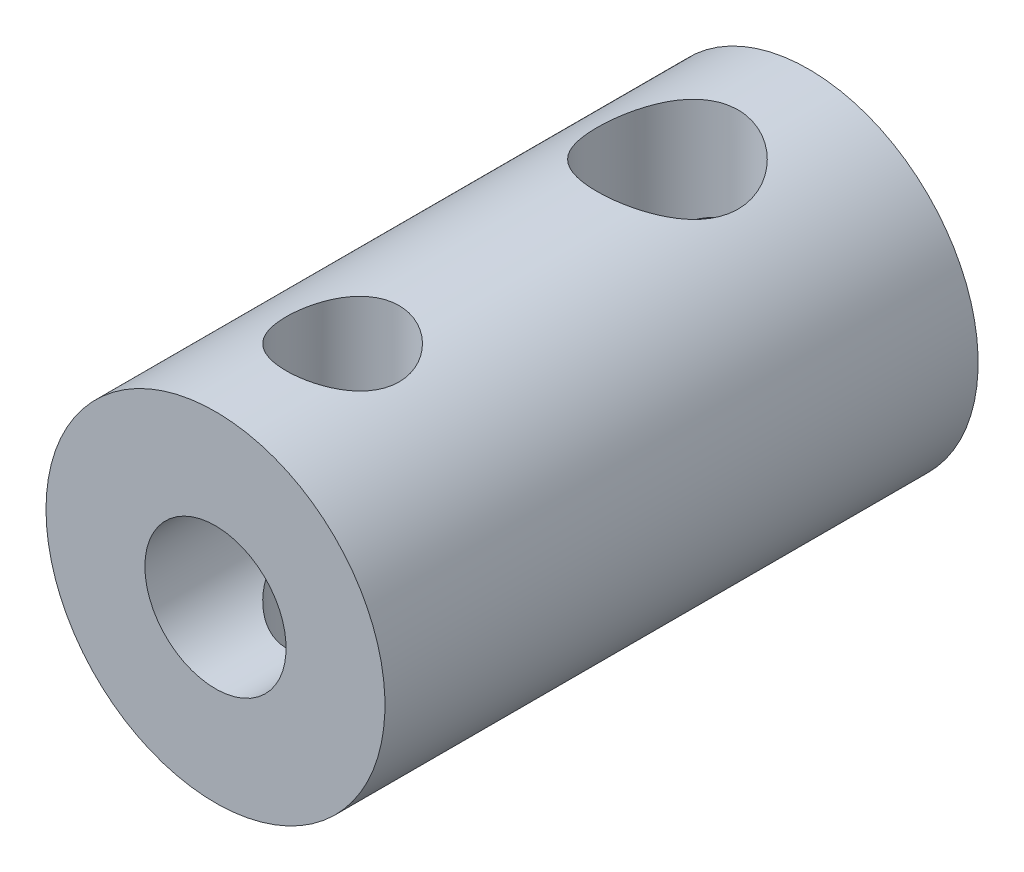
SolidWorks part; units mm, degrees
ref_plane "前视基准面" through (0, 0, 0) normal (0, 0, 1) x (1, 0, 0)
ref_plane "上视基准面" through (0, 0, 0) normal (0, 1, 0) x (1, 0, 0)
ref_plane "右视基准面" through (0, 0, 0) normal (1, 0, 0) x (0, 0, -1)
ref_plane "基准面4" through (0, -40, 0) normal (0, -1, 0) x (1, 0, 0)
sketch "草图1" plane through (0, -40, 0) normal (0, -1, 0) x (1, 0, 0)
  line L0 (15, -10) -> (9, -10)
  line L1 (9, -10) -> (9, -31)
  line L2 (9, -31) -> (15, -31)
  line L3 (15, -31) -> (15, -10)
  line L4 (9, -10) -> (9, -31) construction
revolve "旋转1" add sketch "草图1" angle 360 about L4
hole_wizard "Ø5.0 (5) 直径孔1" positions "草图3" profile "草图2" hole size "Ø5.0" standard "ANSI Metric"
sketch "草图3" plane through (0, 0, -31) normal (0, 0, -1) x (-1, 0, 0)
  point P0 (-9, -40)
sketch "草图2" plane through (9, -40, -31) normal (1, 0, 0) x (0, 1, 0)
  line L0 (0, 0) -> (0, 21)
  line L1 (0, 21) -> (2.5, 21)
  line L2 (2.5, 21) -> (2.5, 0)
  line L5 (2.5, 0) -> (0, 0)
  line L11 (0, -6.35) -> (0, 107.95) construction
  dimension "通孔孔直径" = 5
  dimension "通孔孔深度" = 21
hole_wizard "Ø5.0 (5) 直径孔2" positions "3D草图1" profile "草图4" hole size "Ø5.0" standard "ANSI Metric"
sketch3d "3D草图1"
  point P0 (9, -46, -26)
sketch "草图4" plane through (9, -46, -26) normal (1, 0, 0) x (0, 0, -1)
  line L0 (0, 0) -> (0, 18)
  line L1 (0, 18) -> (2.5, 18)
  line L2 (2.5, 18) -> (2.5, 0)
  line L5 (2.5, 0) -> (0, 0)
  line L10 (0, 18) -> (-2.5, 18) construction
  line L11 (0, -6.35) -> (0, 107.95) construction
  dimension "孔直径" = 5
  dimension "孔深度" = 18
  dimension "导头角度" = 180
ref_plane "基准面5" through (0, -41.5, 0) normal (0, 1, 0) x (1, 0, 0)
hole_wizard "Ø4.0 (4) 直径孔1" positions "草图6" profile "草图5" hole size "Ø4.0" standard "ANSI Metric"
sketch "草图6" plane through (0, -41.5, 0) normal (0, 1, 0) x (1, 0, 0)
  point P0 (9, 14.5)
sketch "草图5" plane through (9, -41.5, -14.5) normal (1, 0, 0) x (0, 0, 1)
  line L0 (0, 0) -> (0, 4.5)
  line L1 (0, 4.5) -> (2, 4.5)
  line L2 (2, 4.5) -> (2, 0)
  line L5 (2, 0) -> (0, 0)
  line L11 (0, -6.35) -> (0, 107.95) construction
  dimension "通孔孔直径" = 4
  dimension "通孔孔深度" = 4.5
ref_plane "基准面6" through (0, -38.5, 0) normal (0, -1, 0) x (-1, 0, 0)
hole_wizard "Ø4.0 (4) 直径孔2" positions "草图8" profile "草图7" hole size "Ø4.0" standard "ANSI Metric"
sketch "草图8" plane through (0, -38.5, 0) normal (0, -1, 0) x (-1, 0, 0)
  point P0 (-9, 14.5)
sketch "草图7" plane through (9, -38.5, -14.5) normal (1, 0, 0) x (0, 0, -1)
  line L0 (0, 0) -> (0, 4.5)
  line L1 (0, 4.5) -> (2, 4.5)
  line L2 (2, 4.5) -> (2, 0)
  line L5 (2, 0) -> (0, 0)
  line L11 (0, -6.35) -> (0, 107.95) construction
  dimension "通孔孔直径" = 4
  dimension "通孔孔深度" = 4.5
